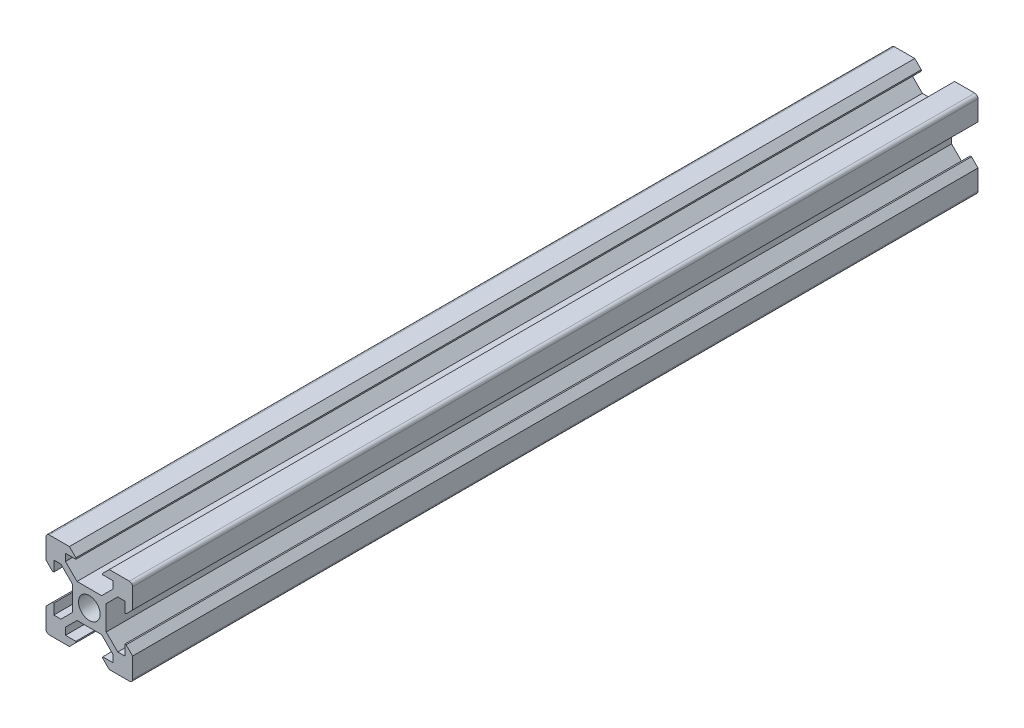
SolidWorks part; units mm, degrees
other "Markup1"
sketch "Sketch1" plane through (10, 10, 480) normal (0.5774, 0.5773, 0.5774) x (0.7071, 0, -0.7071)
ref_plane "Alzado" through (0, 0, 0) normal (0, 0, 1) x (1, 0, 0)
ref_plane "Planta" through (0, 0, 0) normal (0, 1, 0) x (1, 0, 0)
ref_plane "Vista lateral" through (0, 0, 0) normal (1, 0, 0) x (0, 0, -1)
sketch "Croquis1" plane through (0, 0, 0) normal (0, 0, 1) x (1, 0, 0)
  line L0 (-4.6, 10) -> (-3.1, 8.5)
  line L3 (-4.6, 10) -> (-9.25, 10)
  line L5 (-3.1, 8.5) -> (-3.1, 8.2)
  line L6 (-3.1, 8.2) -> (-5.5, 8.2)
  line L7 (-5.5, 8.2) -> (-5.5, 6.5607)
  line L8 (-5.5, 6.5607) -> (-2.84, 3.9007)
  line L9 (-2.84, 3.9007) -> (0, 3.9007)
  line L10 (0, 0) -> (-15.3499, 15.3499) construction
  line L11 (-3.9007, 2.84) -> (-3.9007, 0)
  line L12 (-6.5607, 5.5) -> (-3.9007, 2.84)
  line L13 (-8.2, 5.5) -> (-6.5607, 5.5)
  line L14 (-8.2, 3.1) -> (-8.2, 5.5)
  line L15 (-8.5, 3.1) -> (-8.2, 3.1)
  line L16 (-10, 4.6) -> (-10, 9.25)
  line L17 (-10, 4.6) -> (-8.5, 3.1)
  line L18 (10, 4.6) -> (8.5, 3.1)
  line L19 (10, 4.6) -> (10, 9.25)
  line L20 (8.5, 3.1) -> (8.2, 3.1)
  line L21 (8.2, 3.1) -> (8.2, 5.5)
  line L22 (8.2, 5.5) -> (6.5607, 5.5)
  line L23 (6.5607, 5.5) -> (3.9007, 2.84)
  line L24 (3.9007, 2.84) -> (3.9007, 0)
  line L25 (5.5, 6.5607) -> (2.84, 3.9007)
  line L26 (5.5, 8.2) -> (5.5, 6.5607)
  line L27 (3.1, 8.2) -> (5.5, 8.2)
  line L28 (3.1, 8.5) -> (3.1, 8.2)
  line L29 (4.6, 10) -> (9.25, 10)
  line L30 (4.6, 10) -> (3.1, 8.5)
  line L31 (2.84, 3.9007) -> (0, 3.9007)
  line L32 (4.6, -10) -> (3.1, -8.5)
  line L33 (4.6, -10) -> (9.25, -10)
  line L34 (3.1, -8.5) -> (3.1, -8.2)
  line L35 (3.1, -8.2) -> (5.5, -8.2)
  line L36 (5.5, -8.2) -> (5.5, -6.5607)
  line L37 (5.5, -6.5607) -> (2.84, -3.9007)
  line L38 (2.84, -3.9007) -> (0, -3.9007)
  line L39 (6.5607, -5.5) -> (3.9007, -2.84)
  line L40 (8.2, -5.5) -> (6.5607, -5.5)
  line L41 (8.2, -3.1) -> (8.2, -5.5)
  line L42 (8.5, -3.1) -> (8.2, -3.1)
  line L43 (10, -4.6) -> (10, -9.25)
  line L44 (10, -4.6) -> (8.5, -3.1)
  line L45 (3.9007, -2.84) -> (3.9007, 0)
  line L46 (-10, -4.6) -> (-8.5, -3.1)
  line L47 (-10, -4.6) -> (-10, -9.25)
  line L48 (-8.5, -3.1) -> (-8.2, -3.1)
  line L49 (-8.2, -3.1) -> (-8.2, -5.5)
  line L50 (-8.2, -5.5) -> (-6.5607, -5.5)
  line L51 (-6.5607, -5.5) -> (-3.9007, -2.84)
  line L52 (-3.9007, -2.84) -> (-3.9007, 0)
  line L53 (-5.5, -6.5607) -> (-2.84, -3.9007)
  line L54 (-5.5, -8.2) -> (-5.5, -6.5607)
  line L55 (-3.1, -8.2) -> (-5.5, -8.2)
  line L56 (-3.1, -8.5) -> (-3.1, -8.2)
  line L57 (-4.6, -10) -> (-9.25, -10)
  line L58 (-4.6, -10) -> (-3.1, -8.5)
  line L59 (-2.84, -3.9007) -> (0, -3.9007)
  circle A0 centre (0, 0) radius 2.5
  arc A1 (-9.25, 10) -> (-10, 9.25) centre (-9.25, 9.25) ccw
  arc A2 (10, 9.25) -> (9.25, 10) centre (9.25, 9.25) ccw
  arc A3 (9.25, -10) -> (10, -9.25) centre (9.25, -9.25) ccw
  arc A4 (-10, -9.25) -> (-9.25, -10) centre (-9.25, -9.25) ccw
  point P18 (-10, 10)
  point P37 (10, 10)
  point P55 (10, -10)
  point P73 (-10, -10)
  point P79 (0, 0)
  dimension "D1" = 5
  dimension "D5" = 0.75
  dimension "D2" = 10
  dimension "D3" = 10
  dimension "D4" = 4.6
  dimension "D6" = 5.5
  dimension "D7" = 135
  dimension "D8" = 0.75
  dimension "D9" = 225
  dimension "D10" = 2.84
  dimension "D11" = 1.8
  dimension "D12" = 3.1
  dimension "D13" = 4
extrude "Saliente-Extruir1" add sketch "Croquis1" along normal blind 195.2
